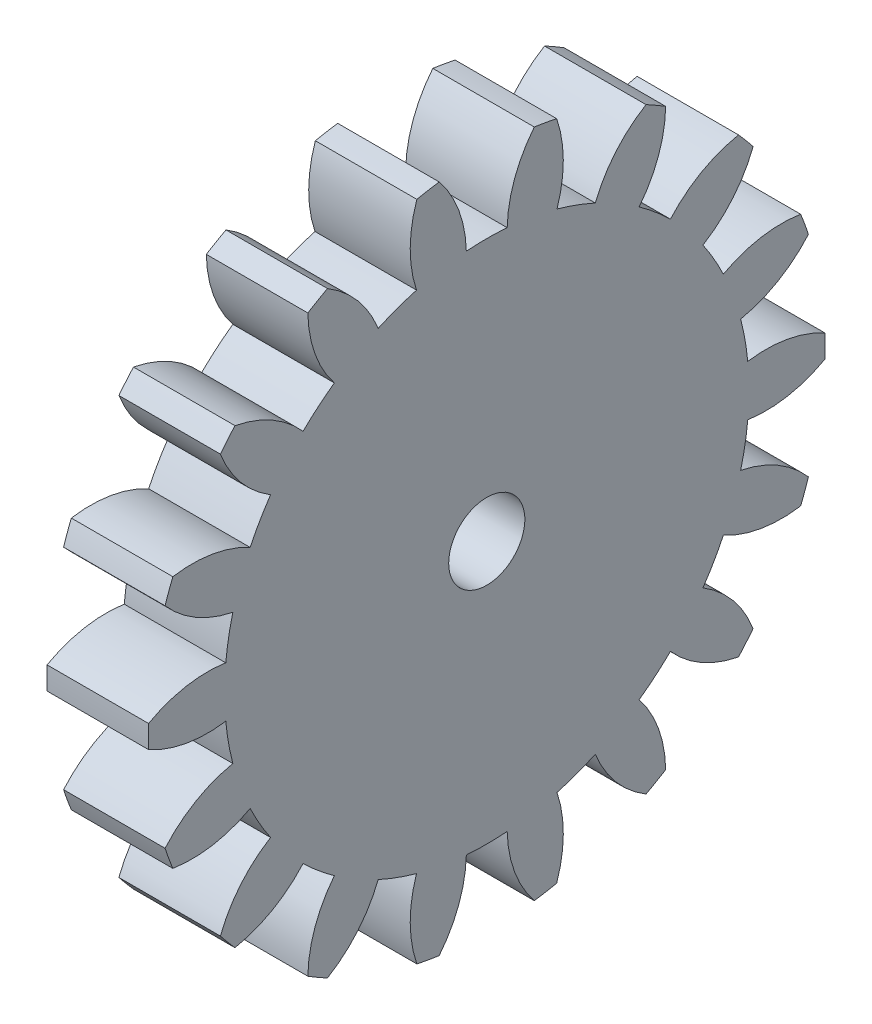
SolidWorks part; units mm, degrees
ref_plane "Plane1" through (0, 0, 0) normal (0, 0, 1) x (1, 0, 0)
ref_plane "Plane2" through (0, 0, 0) normal (0, 1, 0) x (1, 0, 0)
ref_plane "Plane3" through (0, 0, 0) normal (1, 0, 0) x (0, 0, -1)
sketch "HoldingSke" plane through (0, 0, 0) normal (0, 1, 0) x (1, 0, 0)
  line L0 (0, 0) -> (289.882, -94.1884)
  line L1 (-15, 0) -> (100, 0) construction
  line L2 (0, 0) -> (-2.1039, 2.3779)
  line L3 (0, 0) -> (-11.863, 4.5341)
  line L4 (0, 0) -> (8.2133, 2.6687)
  line L5 (0, 0) -> (-11.8993, -4.4381)
  line L6 (0, 0) -> (-5.2639, -3.5516)
  line L7 (-2.1039, 2.3779) -> (0.6298, 14.7802)
  line L8 (-76.2, 54.61) -> (-71.1708, 54.61)
  line L9 (-67.7845, 28.3722) -> (-49.3413, 33.142)
  line L10 (-76.2, 71.12) -> (104.1128, 71.12)
  line L11 (0, 0) -> (-6.35, 0)
  line L12 (-76.2, 101.6) -> (-76.1147, 101.6)
  line L13 (24.9733, 27.94) -> (52.9518, 28.4284)
  line L14 (24.9733, 27.94) -> (24.9746, 27.94)
  line L15 (24.9733, 27.94) -> (100.4006, 29.5858)
  circle A0 centre (0, 0) radius 2.3813
  circle A1 centre (0, 0) radius 6.35
  circle A2 centre (0, 0) radius 6.35
  circle A3 centre (0, 0) radius 2.3813
  dimension "MHD" = 12.7
  dimension "Hub_dia" = 12.7
  dimension "Bore" = 4.7625
  dimension "MBD" = 4.7625
  dimension "Num_teeth" = 18
  dimension "Pitch_radius" = 180.3128
  dimension "Pitch" = 304.8
  dimension "Width" = 6.35
  dimension "Overall_len" = 12.7
  dimension "Show_teeth" = 18
  dimension "Thickness" = 6.35
  dimension "OAL" = 12.7001
  dimension "T_dim" = 5.0292
  dimension "Ap" = 14.5
  dimension "H" = 19.05
  dimension "Backlash" = 0.0853
  dimension "Addendum_fac" = 1
  dimension "Dedendum_fac" = 1.25
  dimension "Clearance_fac" = 0.25
  dimension "Dedendum_add" = 0.0013
sketch "BasProSke" plane through (0, 0, 0) normal (0, 1, 0) x (1, 0, 0)
  line L0 (-10, 0) -> (60, 0) construction
  line L1 (0, 0) -> (0, 21.1667)
  line L2 (0, 0) -> (6.35, 0)
  line L3 (6.35, 0) -> (6.35, 21.1667)
  line L4 (6.35, 21.1667) -> (0, 21.1667)
  dimension "Diameter" = 42.3333
  dimension "Thickness" = 6.35
revolve "Base-Revolve" add sketch "BasProSke" angle 360 about L0
sketch "TooCutSke" plane through (0, 0, 0) normal (1, 0, 0) x (0, 0, -1)
  line L1 (0, 0) -> (0, 107) construction
  line L2 (0, 0) -> (-1.8096, 18.9639) construction
  line L3 (0, 0) -> (-6.5952, 37.403) construction
  line L4 (-1.8096, 18.9639) -> (-3.2976, 18.7015) construction
  arc A0 (1.2763, 16.3532) -> (-1.2763, 16.3532) centre (0, 0) ccw
  arc A1 (2.9939, 20.9795) -> (-2.9939, 20.9795) centre (0, 0) ccw
  circle A2 centre (0, 0) radius 19.05 construction
  circle A3 centre (0, 0) radius 18.4432 construction
  arc A4 (-1.2763, 16.3532) -> (-2.9939, 20.9795) centre (-8.8938, 16.1571) ccw
  arc A5 (2.9939, 20.9795) -> (1.2763, 16.3532) centre (8.8938, 16.1571) ccw
  dimension "Root_dia" = 32.8058
  dimension "Overcut_dia" = 42.3841
  dimension "Pitch_dia" = 38.1
  dimension "Base_dia" = 36.8864
  dimension "Flank_rad" = 7.62
  dimension "Half_ang" = 10
  dimension "Half_CT" = 1.511
extrude "ToothCut" cut sketch "TooCutSke" along normal through all
fillet "Breaks" [suppressed] radius 0.0423
fillet "RootFillets" [suppressed] radius 0.5304
pattern_circular "TeethCuts" count 18 every 20 about axis through (-10, 0, 0) along (1, 0, 0) of "ToothCut", "RootFillets", "Breaks"
sketch "HubNeaOneSke" plane through (0, 0, 0) normal (-1, 0, 0) x (0, 0, 1)
  circle A0 centre (0, 0) radius 6.35
  dimension "Diameter" = 12.7
extrude "HubNearOne" add sketch "HubNeaOneSke" along normal blind 6.3501
sketch "HubNeaBotSke" plane through (0, 0, 0) normal (-1, 0, 0) x (0, 0, 1)
  circle A0 centre (0, 0) radius 6.35
  dimension "Diameter" = 12.7
extrude "HubNearBoth" [suppressed] add sketch "HubNeaBotSke" along normal blind 3.175
ref_plane "FarPln" through (6.35, 0, 0) normal (1, 0, 0) x (0, 0, -1)
sketch "HubFarSke" plane through (6.35, 0, 0) normal (1, 0, 0) x (0, 0, -1)
  circle A0 centre (0, 0) radius 6.35
  dimension "Diameter" = 12.7
extrude "HubFar" [suppressed] add sketch "HubFarSke" along normal blind 3.175
sketch "BorSke" plane through (0, 0, 0) normal (1, 0, 0) x (0, 0, -1)
  circle A0 centre (0, 0) radius 2.3813
  dimension "Diameter" = 4.7625
extrude "Bore" cut sketch "BorSke" along normal mid plane 25.4001
sketch "KeySke" plane through (0, 0, 0) normal (1, 0, 0) x (0, 0, -1)
  line L0 (-0.127, 0) -> (-0.127, 2.6479)
  line L1 (-0.127, 2.6479) -> (0.127, 2.6479)
  line L2 (0.127, 2.6479) -> (0.127, 0)
  line L3 (0, 0) -> (0, 34) construction
  line L4 (-0.127, 0) -> (0.127, 0)
  dimension "Offset" = 2.6479
  dimension "Width" = 0.254
extrude "Keyway" [suppressed] cut sketch "KeySke" along normal mid plane 25.4001
pattern_circular "Keyway2" [suppressed] count 2 every 90 about axis through (-10, 0, 0) along (1, 0, 0)
equation "' \"Pitch@HoldingSke\" = 4"
equation "' \"Num_teeth@HoldingSke\" = 12"
equation "' \"Ap@HoldingSke\" =  20"
equation "' \"Width@HoldingSke\" = 0.5"
equation "' \"Hub_dia@HoldingSke\"= 1"
equation "' \"Overall_len@HoldingSke\" = 1.0"
equation "' \"Bore@HoldingSke\" = 0.75"
equation "' \"T_dim@HoldingSke\" = 0.85"
equation "' \"Width@KeySke\" = 0.25"
equation "' \"Show_teeth@HoldingSke\" = 13"
equation "' \"Backlash@HoldingSke\" = 0.009"
equation "' \"Addendum_fac@HoldingSke\" = 1.0"
equation "' \"Dedendum_fac@HoldingSke\" = 1.25"
equation "' \"Dedendum_add@HoldingSke\" = 0.00005"
equation "' \"Clearance_fac@HoldingSke\" = 0.25"
equation "' \"Pitch@HoldingSke\" = 0.5"
equation "' \"Num_teeth@HoldingSke\" = 23"
equation "' \"Show_teeth@HoldingSke\" = 23"
equation "' \"Backlash@HoldingSke\" = 0.0375"
equation "\"Overcut_dia@TooCutSke\" = (\"Num_teeth@HoldingSke\" + 2 * \"Addendum_fac@HoldingSke\") / \"Pitch@HoldingSke\" + 0.002"
equation "\"Pitch_dia@TooCutSke\" = \"Num_teeth@HoldingSke\" / \"Pitch@HoldingSke\""
equation "\"Base_dia@TooCutSke\" = \"Num_teeth@HoldingSke\" / \"Pitch@HoldingSke\" * cos((\"Ap@HoldingSke\"  * 3.14159265 / 180))"
equation "\"Root_dia@TooCutSke\" = (\"Num_teeth@HoldingSke\" + 2) / \"Pitch@HoldingSke\" - 2 * (\"Addendum_fac@HoldingSke\" + \"Dedendum_fac@HoldingSke\") / \"Pitch@HoldingSke\" - \"Dedendum_add@HoldingSke\" * 2"
equation "\"Half_ang@TooCutSke\" = 180 / \"Num_teeth@HoldingSke\""
equation "\"Half_CT@TooCutSke\" = \"Num_teeth@HoldingSke\" / \"Pitch@HoldingSke\" * sin((3.14159265 / 2 / \"Num_teeth@HoldingSke\")) / 2 - 7 * \"Backlash@HoldingSke\" / 4"
equation "\"Flank_rad@TooCutSke\" = \"Num_teeth@HoldingSke\" / \"Pitch@HoldingSke\" / 5"
equation "\"Radius@RootFillets\" = \"Clearance_fac@HoldingSke\" / \"Pitch@HoldingSke\" + \"Dedendum_add@HoldingSke\""
equation "\"Break_rad@Breaks\" = 0.02 / \"Pitch@HoldingSke\""
equation "\"Thickness@HoldingSke\" = \"Width@HoldingSke\""
equation "\"OAL@HoldingSke\" = \"Thickness@HoldingSke\""
equation "\"MHD@HoldingSke\" = (\"Num_teeth@HoldingSke\" + 2) / \"Pitch@HoldingSke\" - 2 * (\"Addendum_fac@HoldingSke\" + \"Dedendum_fac@HoldingSke\")  / \"Pitch@HoldingSke\" - \"Dedendum_add@HoldingSke\" * 2"
equation "\"MBD@HoldingSke\" = (\"Num_teeth@HoldingSke\" + 2) / \"Pitch@HoldingSke\" - 2 * (\"Addendum_fac@HoldingSke\" + \"Dedendum_fac@HoldingSke\")  / \"Pitch@HoldingSke\" - \"Dedendum_add@HoldingSke\" * 2 - 0.002"
equation "\"MHD@HoldingSke\" = ((sgn( \"MHD@HoldingSke\" - \"Hub_dia@HoldingSke\" )-1)*( \"MHD@HoldingSke\" - \"Hub_dia@HoldingSke\" ))/-2+ \"Hub_dia@HoldingSke\""
equation "\"MBD@HoldingSke\" = ((sgn( \"MBD@HoldingSke\" - \"Bore@HoldingSke\" )-1)*( \"MBD@HoldingSke\" - \"Bore@HoldingSke\" ))/-2+ \"Bore@HoldingSke\""
equation "\"OAL@HoldingSke\" = ((sgn( \"OAL@HoldingSke\" - \"Overall_len@HoldingSke\" )+1)*( \"OAL@HoldingSke\" - \"Overall_len@HoldingSke\" ))/2 + \"Overall_len@HoldingSke\" + 0.000002"
equation "\"Num_teeth@TeethCuts\" = int( \"Show_teeth@HoldingSke\" ) + 1"
equation "\"Num_teeth@TeethCuts\" = ((sgn( \"Num_teeth@TeethCuts\" - \"Num_teeth@HoldingSke\" )-1)*( \"Num_teeth@TeethCuts\" - \"Num_teeth@HoldingSke\" ))/-2+ \"Num_teeth@HoldingSke\""
equation "\"Num_teeth@TeethCuts\" = ((sgn( \"Num_teeth@TeethCuts\" - 2.0)+1)*( \"Num_teeth@TeethCuts\" - 2.0))/2 +2.0"
equation "\"Angle@TeethCuts\" = 360.0 / \"Num_teeth@HoldingSke\""
equation "\"Diameter@BasProSke\" = (\"Num_teeth@HoldingSke\" + 2 * \"Addendum_fac@HoldingSke\") / \"Pitch@HoldingSke\""
equation "\"Thickness@BasProSke\"  = \"Thickness@HoldingSke\""
equation "' \"Fillet_rad@BasProSke\" =  \"Thickness@HoldingSke\" * 0.05"
equation "\"MHD@HoldingSke\" = ((sgn( \"MHD@HoldingSke\" - \"Root_dia@TooCutSke\" )-1)*( \"MHD@HoldingSke\" - \"Root_dia@TooCutSke\" ))/-2+ \"Root_dia@TooCutSke\""
equation "\"Diameter@HubNeaOneSke\" = \"MHD@HoldingSke\""
equation "\"Length@HubNearOne\" = \"OAL@HoldingSke\" - \"Thickness@BasProSke\""
equation "\"Diameter@HubNeaBotSke\" = \"MHD@HoldingSke\""
equation "\"Length@HubNearBoth\" = ( \"OAL@HoldingSke\" - \"Thickness@BasProSke\" ) / 2.0"
equation "\"Thickness@FarPln\" = \"Thickness@BasProSke\""
equation "\"Diameter@HubFarSke\" = \"MHD@HoldingSke\""
equation "\"Length@HubFar\" = ( \"OAL@HoldingSke\" - \"Thickness@BasProSke\" ) / 2.0"
equation "\"Diameter@BorSke\" = \"MBD@HoldingSke\""
equation "\"D1@Bore\" = \"OAL@HoldingSke\" * 2.0"
equation "\"D1@Keyway\" = \"OAL@HoldingSke\" * 2.0"
equation "\"Offset@KeySke\" = \"T_dim@HoldingSke\" - \"MBD@HoldingSke\" / 2.0"
